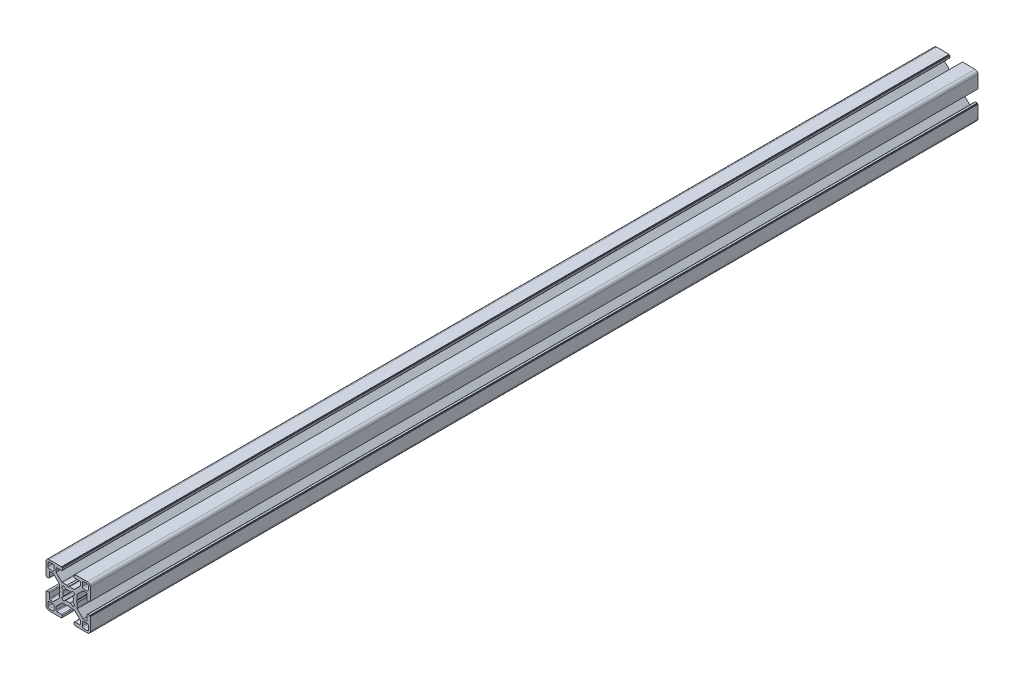
SolidWorks part; units mm, degrees
ref_plane "Front Plane" through (0, 0, 0) normal (0, 0, 1) x (1, 0, 0)
ref_plane "Top Plane" through (0, 0, 0) normal (0, 1, 0) x (1, 0, 0)
ref_plane "Right Plane" through (0, 0, 0) normal (1, 0, 0) x (0, 0, -1)
sketch "Sketch1" plane through (0, 0, 0) normal (0, 0, 1) x (1, 0, 0)
  line L0 (-15, 0) -> (15, 0) construction
  line L1 (0, -15) -> (0, 15) construction
  line L2 (-4.5, 15) -> (4.5, 15) construction
  line L3 (-4, -15) -> (4, -15) construction
  line L4 (-4.5, 15) -> (-4.5, 14.5)
  line L5 (-4.5, 14.5) -> (-4, 14.5)
  line L6 (-4, 14.5) -> (-4, 13.29)
  line L7 (-4.5, 12.79) -> (-7.7675, 12.79)
  line L8 (-8.2675, 12.29) -> (-8.2675, 10.2707)
  line L9 (-8.1211, 9.9171) -> (-4.3504, 6.1464)
  line L10 (-3.9968, 6) -> (0, 6)
  line L11 (0, 0) -> (-15, 15) construction
  line L12 (-4.5, 15) -> (-12.968, 15)
  line L14 (-12.705, 9.5135) -> (-10.5135, 9.5135)
  line L15 (-13.705, 10.5135) -> (-13.705, 12.705)
  line L16 (-12.705, 13.705) -> (-10.5135, 13.705)
  line L17 (-9.5135, 10.5135) -> (-9.5135, 12.705)
  line L18 (-13.705, 9.5135) -> (-9.5135, 13.705) construction
  line L19 (-13.705, 13.705) -> (-9.5135, 9.5135) construction
  line L20 (-3.1568, 4.5038) -> (-1.5303, 3.1477) construction
  line L21 (-4.5038, 3.1568) -> (-3.1477, 1.5303) construction
  line L22 (-6, 3.9968) -> (-6, 0)
  line L23 (-9.9171, 8.1211) -> (-6.1464, 4.3504)
  line L24 (-15, 4.5) -> (-15, 12.968)
  line L25 (-12.29, 8.2675) -> (-10.2707, 8.2675)
  line L26 (-12.79, 4.5) -> (-12.79, 7.7675)
  line L27 (-14.5, 4) -> (-13.29, 4)
  line L28 (-14.5, 4.5) -> (-14.5, 4)
  line L29 (-15, 4.5) -> (-14.5, 4.5)
  circle A0 centre (0, 0) radius 3.5
  arc A1 (-12.968, 15) -> (-15, 12.968) centre (-12.968, 12.968) ccw
  circle A2 centre (0, 0) radius 5.5 construction
  arc A3 (-10.5135, 9.5135) -> (-9.5135, 10.5135) centre (-10.5135, 10.5135) ccw
  arc A4 (-13.705, 12.705) -> (-12.705, 13.705) centre (-12.705, 12.705) cw
  arc A5 (-10.5135, 13.705) -> (-9.5135, 12.705) centre (-10.5135, 12.705) cw
  arc A6 (-12.705, 9.5135) -> (-13.705, 10.5135) centre (-12.705, 10.5135) cw
  arc A7 (-12.79, 4.5) -> (-13.29, 4) centre (-13.29, 4.5) cw
  arc A8 (-12.29, 8.2675) -> (-12.79, 7.7675) centre (-12.29, 7.7675) ccw
  arc A9 (-9.9171, 8.1211) -> (-10.2707, 8.2675) centre (-10.2707, 7.7675) ccw
  arc A10 (-6, 3.9968) -> (-6.1464, 4.3504) centre (-6.5, 3.9968) ccw
  arc A11 (-4.3504, 6.1464) -> (-3.9968, 6) centre (-3.9968, 6.5) ccw
  arc A12 (-4, 13.29) -> (-4.5, 12.79) centre (-4.5, 13.29) cw
  arc A13 (-7.7675, 12.79) -> (-8.2675, 12.29) centre (-7.7675, 12.29) ccw
  arc A14 (-8.2675, 10.2707) -> (-8.1211, 9.9171) centre (-7.7675, 10.2707) ccw
  point P4 (0, 0)
  point P8 (0, 0)
  point P13 (0, 15)
  point P15 (0, -15)
  point P16 (0, 6)
  point P23 (-11.6092, 11.6093)
  point P26 (0, 6)
  point P62 (-12.79, 4)
  point P65 (-12.79, 8.2675)
  point P68 (-10.0636, 8.2675)
  point P71 (-6, 4.2039)
  point P74 (-4.2039, 6)
  point P77 (-4, 12.79)
  point P80 (-8.2675, 12.79)
  point P83 (-8.2675, 10.0636)
  dimension "Center Hole Diameter" = 7
  dimension "D11" = 2.032
  dimension "D9" = 11
  dimension "D13" = 1
  dimension "D14" = 0.5
  dimension "Rail Height" = 30
  dimension "Rail Width" = 30
  dimension "T-Slot Width" = 8
  dimension "T-Slot Depth" = 9
  dimension "D1" = 9
  dimension "D2" = 45
  dimension "D3" = 8
  dimension "D4" = 2.21
  dimension "D5" = 16.535
  dimension "D7" = 2.54
  dimension "D6" = 1.295
  dimension "D8" = 1.246
  dimension "D10" = 10.36
  dimension "D12" = 1.905
sketch "Sketch2" plane through (0, 0, 0) normal (1, 0, 0) x (0, 0, -1)
  line L0 (-76.2, 0) -> (76.2, 0) construction
  line L2 (0, -15) -> (0, 15) construction
  line L3 (0, -15) -> (0, 15) construction
  line L4 (-76.2, -15) -> (-76.2, 15) construction
  line L5 (76.2, -15) -> (76.2, 15) construction
  point P0 (-38.7, 0)
  point P3 (0, 0)
  point P4 (38.7, 0)
  point P12 (-76.2, 0)
  point P14 (76.2, 0)
  dimension "Length" = 152.4
  dimension "D1" = 37.5
sketch "Sketch3" plane through (0, 0, 0) normal (0, 0, 1) x (1, 0, 0)
  line L0 (-4.5038, 3.1568) -> (-3.1477, 1.5303)
  line L1 (0, 3.5) -> (0, 5.5)
  line L2 (-5.5, 0) -> (-3.5, 0)
  line L7 (-6, 3.9968) -> (-6, 0) construction
  line L31 (-9.9171, 8.1211) -> (-6.1464, 4.3504) construction
  line L117 (-12.29, 8.2675) -> (-10.2707, 8.2675) construction
  line L118 (-12.79, 4.5) -> (-12.79, 7.7675) construction
  line L157 (-12.705, 9.5135) -> (-10.5135, 9.5135)
  line L158 (-9.5135, 10.5135) -> (-9.5135, 12.705)
  line L163 (-10.5135, 13.705) -> (-12.705, 13.705)
  line L164 (-13.705, 12.705) -> (-13.705, 10.5135)
  line L165 (-12.705, 9.5135) -> (-10.5135, 9.5135)
  line L166 (-9.5135, 10.5135) -> (-9.5135, 12.705)
  line L167 (-10.5135, 13.705) -> (-12.705, 13.705)
  line L168 (-13.705, 12.705) -> (-13.705, 10.5135)
  line L169 (-14.5, 4) -> (-13.29, 4) construction
  line L170 (-14.5, 4.5) -> (-14.5, 4) construction
  line L171 (-15, 4.5) -> (-14.5, 4.5) construction
  line L172 (-15, 4.5) -> (-15, 12.968) construction
  line L173 (-4.5, 15) -> (-12.968, 15) construction
  line L174 (-4.5, 15) -> (-4.5, 14.5) construction
  line L175 (-4.5, 14.5) -> (-4, 14.5) construction
  line L176 (-4, 14.5) -> (-4, 13.29) construction
  line L177 (-4.5, 12.79) -> (-7.7675, 12.79) construction
  line L178 (-8.2675, 12.29) -> (-8.2675, 10.2707) construction
  line L179 (-8.1211, 9.9171) -> (-4.3504, 6.1464) construction
  line L180 (-3.9968, 6) -> (0, 6) construction
  line L181 (-6, 3.9968) -> (-6, 0.866)
  line L182 (-9.9171, 8.1211) -> (-6.1464, 4.3504)
  line L183 (-12.29, 8.2675) -> (-10.2707, 8.2675)
  line L184 (-12.79, 4.5) -> (-12.79, 7.7675)
  line L185 (-14.5, 4) -> (-13.29, 4)
  line L186 (-14.5, 4.5) -> (-14.5, 4)
  line L187 (-15, 4.5) -> (-14.5, 4.5)
  line L188 (-15, 4.5) -> (-15, 12.968)
  line L189 (-4.5, 15) -> (-12.968, 15)
  line L190 (-4.5, 15) -> (-4.5, 14.5)
  line L191 (-4.5, 14.5) -> (-4, 14.5)
  line L192 (-4, 14.5) -> (-4, 13.29)
  line L193 (-4.5, 12.79) -> (-7.7675, 12.79)
  line L194 (-8.2675, 12.29) -> (-8.2675, 10.2707)
  line L195 (-8.1211, 9.9171) -> (-4.3504, 6.1464)
  line L196 (-3.9968, 6) -> (-0.866, 6)
  line L197 (-0.866, 6) -> (0, 5.5)
  line L198 (0, -15) -> (0, 15) construction
  line L199 (0, 0) -> (-15, 15) construction
  line L200 (0, 0) -> (-15, 15) construction
  line L201 (-3.1568, 4.5038) -> (-1.5303, 3.1477) construction
  line L202 (-3.1568, 4.5038) -> (-1.5303, 3.1477)
  line L203 (-6, 0.866) -> (-5.5, 0)
  line L204 (-15, 0) -> (15, 0) construction
  line L205 (-15, 0) -> (15, 0) construction
  line L206 (0, -15) -> (0, 15) construction
  arc A0 (-3.5, 0) -> (-3.1477, 1.5303) centre (0, 0) cw
  arc A10 (-6, 3.9968) -> (-6.1464, 4.3504) centre (-6.5, 3.9968) ccw construction
  circle A16 centre (0, 0) radius 3.5
  arc A18 (0, 3.5) -> (-1.5303, 3.1477) centre (0, 0) ccw
  arc A20 (-9.9171, 8.1211) -> (-10.2707, 8.2675) centre (-10.2707, 7.7675) ccw construction
  arc A22 (-12.29, 8.2675) -> (-12.79, 7.7675) centre (-12.29, 7.7675) ccw construction
  arc A28 (-13.29, 4) -> (-12.79, 4.5) centre (-13.29, 4.5) ccw construction
  arc A29 (-10.5135, 9.5135) -> (-9.5135, 10.5135) centre (-10.5135, 10.5135) ccw
  arc A30 (-9.5135, 12.705) -> (-10.5135, 13.705) centre (-10.5135, 12.705) ccw
  arc A31 (-12.705, 13.705) -> (-13.705, 12.705) centre (-12.705, 12.705) ccw
  arc A32 (-13.705, 10.5135) -> (-12.705, 9.5135) centre (-12.705, 10.5135) ccw
  arc A33 (-10.5135, 9.5135) -> (-9.5135, 10.5135) centre (-10.5135, 10.5135) ccw
  arc A34 (-9.5135, 12.705) -> (-10.5135, 13.705) centre (-10.5135, 12.705) ccw
  arc A35 (-12.705, 13.705) -> (-13.705, 12.705) centre (-12.705, 12.705) ccw
  arc A36 (-13.705, 10.5135) -> (-12.705, 9.5135) centre (-12.705, 10.5135) ccw
  arc A37 (-12.968, 15) -> (-15, 12.968) centre (-12.968, 12.968) ccw construction
  arc A38 (-4.5, 12.79) -> (-4, 13.29) centre (-4.5, 13.29) ccw construction
  arc A39 (-7.7675, 12.79) -> (-8.2675, 12.29) centre (-7.7675, 12.29) ccw construction
  arc A40 (-8.2675, 10.2707) -> (-8.1211, 9.9171) centre (-7.7675, 10.2707) ccw construction
  arc A41 (-4.3504, 6.1464) -> (-3.9968, 6) centre (-3.9968, 6.5) ccw construction
  arc A42 (-6, 3.9968) -> (-6.1464, 4.3504) centre (-6.5, 3.9968) ccw
  arc A43 (-9.9171, 8.1211) -> (-10.2707, 8.2675) centre (-10.2707, 7.7675) ccw
  arc A44 (-12.29, 8.2675) -> (-12.79, 7.7675) centre (-12.29, 7.7675) ccw
  arc A45 (-13.29, 4) -> (-12.79, 4.5) centre (-13.29, 4.5) ccw
  arc A46 (-12.968, 15) -> (-15, 12.968) centre (-12.968, 12.968) ccw
  arc A47 (-4.5, 12.79) -> (-4, 13.29) centre (-4.5, 13.29) ccw
  arc A48 (-7.7675, 12.79) -> (-8.2675, 12.29) centre (-7.7675, 12.29) ccw
  arc A49 (-8.2675, 10.2707) -> (-8.1211, 9.9171) centre (-7.7675, 10.2707) ccw
  arc A50 (-4.3504, 6.1464) -> (-3.9968, 6) centre (-3.9968, 6.5) ccw
  circle A51 centre (0, 0) radius 5.5 construction
  arc A52 (-3.1568, 4.5038) -> (-4.5038, 3.1568) centre (0, 0) ccw
  dimension "D3" = 60
  dimension "D4" = 60
  dimension "D1" = 0
  dimension "D2" = 0
extrude "Boss-Extrude1" add sketch "Sketch3" along normal mid plane 600
pattern_circular "CirPattern1" count 4 over 360 about axis through (0, 0, 0) along (0, 0, 1) of "Boss-Extrude1"
ref_plane "Contact Plane1" through (15, 0, 0) normal (1, 0, 0) x (0, 0, -1)
ref_plane "Contact Plane2" through (0, -15, 0) normal (0, 1, 0) x (1, 0, 0)
ref_plane "Contact Plane3" through (-15, 0, 0) normal (1, 0, 0) x (0, 0, -1)
ref_plane "Contact Plane4" through (0, 15, 0) normal (0, 1, 0) x (1, 0, 0)
equation "\"D1@Sketch2\" = \"Rail Height@Sketch1\" * 1.25"
equation "\"D1@Sketch1\"=\"T-Slot Width@Sketch1\"+1mm"
equation "\"D3@Sketch1\"=\"T-Slot Width@Sketch1\""
equation "\"D1@Boss-Extrude1\"=\"Length\""
equation "\"Length\"= 600mm"
